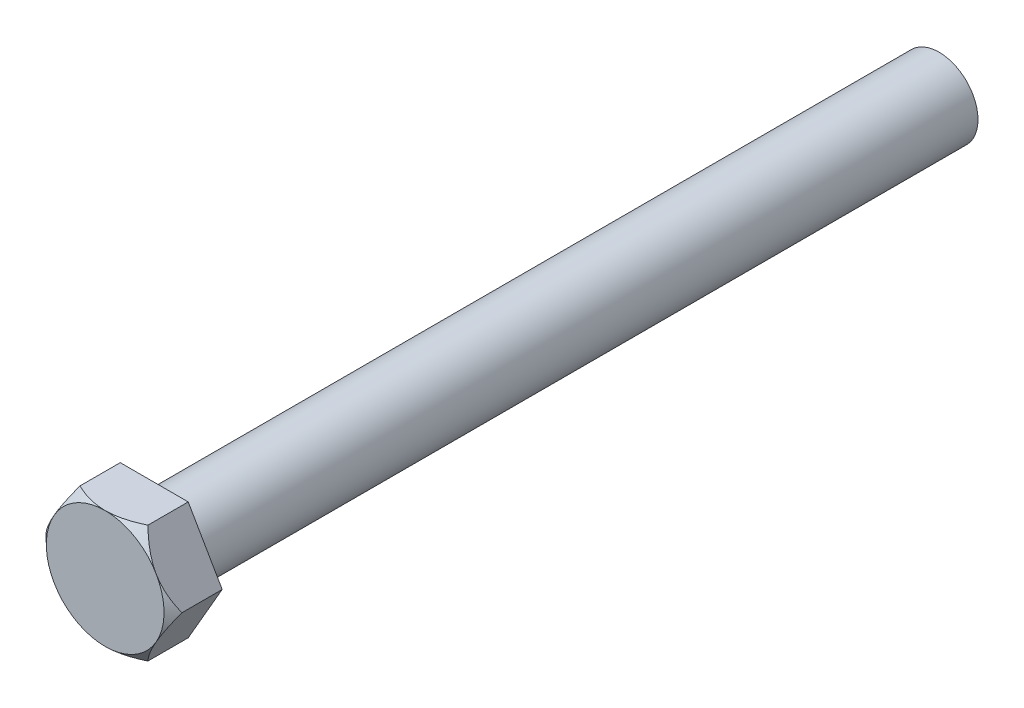
SolidWorks part; units mm, degrees
ref_plane "Alzado" through (0, 0, 0) normal (0, 0, 1) x (1, 0, 0)
ref_plane "Planta" through (0, 0, 0) normal (0, 1, 0) x (1, 0, 0)
ref_plane "Vista lateral" through (0, 0, 0) normal (1, 0, 0) x (0, 0, -1)
sketch "Croquis1" plane through (0, 0, 0) normal (0, 0, 1) x (1, 0, 0)
  circle A0 centre (0, 0) radius 7.9375
  dimension "D1" = 15.875
extrude "Saliente-Extruir1" add sketch "Croquis1" along normal blind 160
sketch "Croquis2" plane through (0, 0, 160) normal (0, 0, 1) x (1, 0, 0)
  line L1 (13.8564, 0) -> (6.9282, 12)
  line L2 (6.9282, 12) -> (-6.9282, 12)
  line L3 (-6.9282, 12) -> (-13.8564, 0)
  line L4 (-13.8564, 0) -> (-6.9282, -12)
  line L5 (-6.9282, -12) -> (6.9282, -12)
  line L6 (6.9282, -12) -> (13.8564, 0)
  circle A0 centre (0, 0) radius 12 construction
  dimension "D1" = 24
extrude "Saliente-Extruir2" add sketch "Croquis2" along normal blind 10
sketch "Croquis3" plane through (0, 0, 170) normal (0, 0, 1) x (1, 0, 0)
  circle A0 centre (0, 0) radius 12
  circle A1 centre (0, 0) radius 34.9216
extrude "Cortar-Extruir1" cut sketch "Croquis3" against normal blind 6 draft 46
